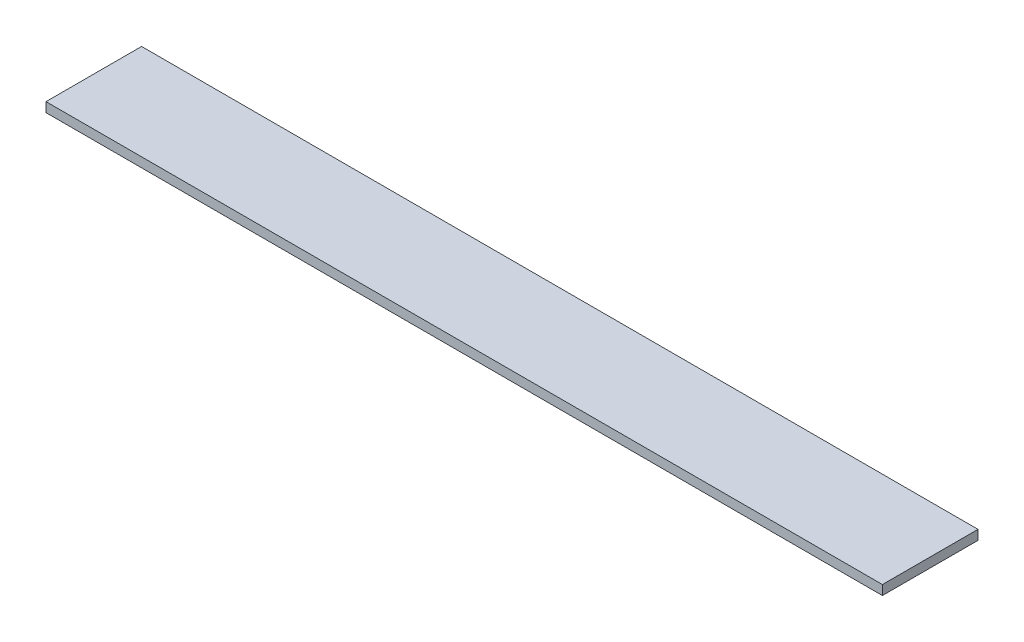
SolidWorks part; units mm, degrees
ref_plane "Front Plane" through (0, 0, 0) normal (0, 0, 1) x (1, 0, 0)
ref_plane "Top Plane" through (0, 0, 0) normal (0, 1, 0) x (1, 0, 0)
ref_plane "Right Plane" through (0, 0, 0) normal (1, 0, 0) x (0, 0, -1)
sketch "Эскиз1" plane through (0, 0, 0) normal (0, 1, 0) x (1, 0, 0)
  line L1 (0, 0) -> (350, 0)
  line L2 (0, 0) -> (0, 40)
  line L3 (0, 40) -> (350, 40)
  line L4 (350, 0) -> (350, 40)
  dimension "D1" = 40
  dimension "D2" = 350
extrude "Бобышка-Вытянуть1" add sketch "Эскиз1" along normal blind 4
